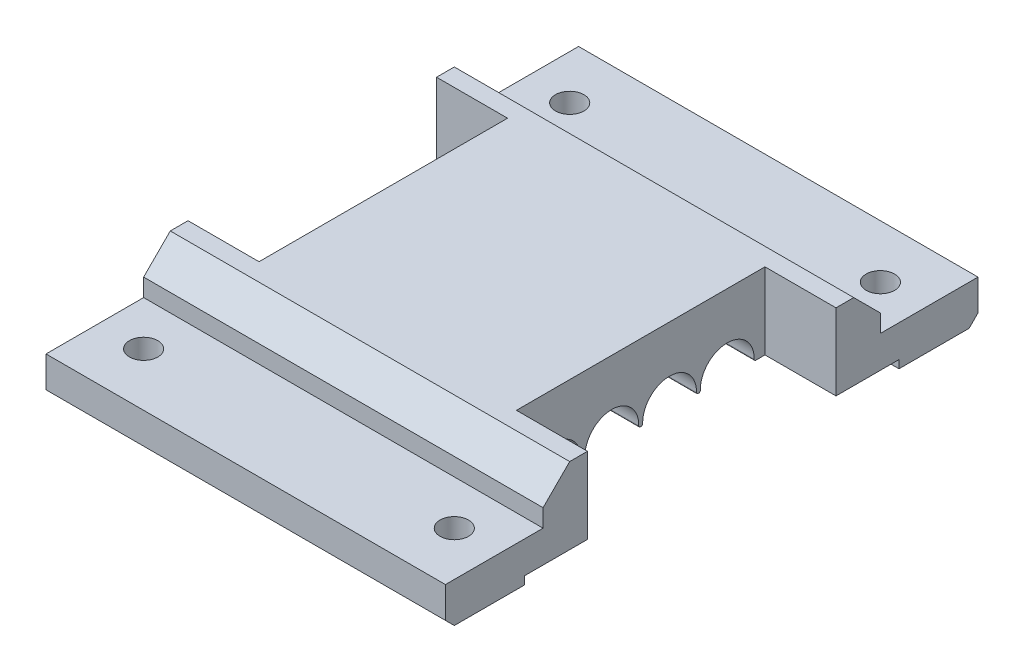
SolidWorks part; units mm, degrees
ref_plane "Front" through (0, 0, 0) normal (0, 0, 1) x (1, 0, 0)
ref_plane "Top" through (0, 0, 0) normal (0, 1, 0) x (1, 0, 0)
ref_plane "Right" through (0, 0, 0) normal (1, 0, 0) x (0, 0, -1)
sketch "Sketch1" plane through (0, 0, 0) normal (0, 1, 0) x (1, 0, 0)
  line L0 (0, -30) -> (0, 30) construction
  line L1 (-22.5, 30) -> (22.5, 30)
  line L2 (-22.5, 30) -> (-22.5, -30)
  line L3 (-22.5, -30) -> (22.5, -30)
  line L4 (22.5, 30) -> (22.5, -30)
  line L5 (-22.5, 30) -> (22.5, -30) construction
  line L6 (-22.5, -30) -> (22.5, 30) construction
  line L7 (-22.5, 24) -> (17.5, 24) construction
  line L8 (22.5, 0) -> (-22.5, 0) construction
  line L9 (17.5, 24) -> (17.5, -30) construction
  circle A0 centre (17.5, 24) radius 1.6
  circle A1 centre (-17.5, 24) radius 1.6
  circle A2 centre (-17.5, -24) radius 1.6
  circle A3 centre (17.5, -24) radius 1.6
  point P0 (0, 0)
  dimension "D1" = 60
extrude "Boss-Extrude1" add sketch "Sketch1" along normal blind 4.5
chamfer "Chamfer1" distance 1 angle 45 2 edges at (0, 0, -30) (0, 0, 30)
sketch "Sketch2" plane through (0, 0, 0) normal (1, 0, 0) x (0, 0, -1)
  line L1 (21.1, -0.9) -> (-21.1, -0.9)
  line L2 (21.1, -0.9) -> (21.1, 0.9)
  line L3 (21.1, 0.9) -> (-21.1, 0.9)
  line L4 (-21.1, -0.9) -> (-21.1, 0.9)
  line L5 (21.1, -0.9) -> (-21.1, 0.9) construction
  line L6 (21.1, 0.9) -> (-21.1, -0.9) construction
  point P0 (0, 0)
extrude "Cut-Extrude1" cut sketch "Sketch2" against normal through all both and the other way through all
sketch "Sketch3" plane through (0, 0, 0) normal (1, 0, 0) x (0, 0, -1)
  line L0 (18.8, -3.6) -> (-18.8, -3.6)
  line L1 (19, -3.4) -> (-19, -3.4)
  line L2 (-21.1, 0) -> (-21.1, 0.9)
  line L3 (-21, 0.9) -> (-21, -2.9)
  line L4 (20.8, -3.1) -> (-20.8, -3.1)
  line L5 (21, -2.9) -> (-21, -2.9)
  line L6 (-19.5, -3.1) -> (-19.5, 0.9)
  line L7 (-19, 6.5) -> (-19, 4.5)
  line L8 (-19, -3.1) -> (-19, -3.4)
  line L9 (21.1, 0.9) -> (12.979, 0.9)
  line L10 (19.5, 0.9) -> (12.762, 0.9)
  line L11 (6.521, 0.9) -> (6.479, 0.9)
  line L12 (6.738, 0.9) -> (6.2718, 0.9)
  line L13 (-0.0213, 0.9) -> (-0.238, 0.9)
  line L14 (-6.262, 0.9) -> (-6.7282, 0.9)
  line L15 (-6.479, 0.9) -> (-6.521, 0.9)
  line L16 (-13.0213, 0.9) -> (-19.5, 0.9)
  line L17 (-13.0213, 0.9) -> (-21.1, 0.9)
  line L18 (-16.5, -3.6) -> (-16.5, -3.1)
  line L19 (16, 9.5) -> (1.9528, 9.5)
  line L20 (-4.9695, 9.5) -> (-11.0472, 9.5)
  line L21 (-17.2502, 8.2498) -> (-19, 6.5)
  line L22 (19, 6.5) -> (16, 9.5)
  line L23 (16.5, -3.6) -> (16.5, -3.1)
  line L24 (19, -3.1) -> (19, -3.4)
  line L25 (19, 4.5) -> (19, 6.5)
  line L26 (19.5, -3.1) -> (19.5, 0.9)
  line L27 (21, 0.9) -> (21, -2.9)
  line L28 (21.1, 0) -> (21.1, 0.9)
  line L29 (12.314, -0.3291) -> (12.4926, -0.0188)
  line L30 (-13.1641, -3.6) -> (-13.1641, -3.1) construction
  arc A0 (-21, -2.9) -> (-20.8, -3.1) centre (-20.8, -2.9) ccw
  arc A1 (-19, -3.4) -> (-18.8, -3.6) centre (-18.8, -3.4) ccw
  arc A2 (-12.5076, -0.0255) -> (-11.4866, -1.2529) centre (-9.75, 1.23) ccw
  arc A3 (-1.5134, -1.2529) -> (-0.238, 0.9) centre (-3.25, 1.23) ccw
  arc A4 (-1.639, 3.7462) -> (-6.0484, 2.3419) centre (-3.25, 1.18) ccw
  arc A5 (-0.2209, 1.105) -> (-0.2215, 1.2756) centre (-3.25, 1.18) ccw
  arc A6 (-6.8667, 2.1113) -> (-7.2516, 2.8943) centre (-9.75, 1.18) ccw
  arc A7 (-1.5536, 3.6161) -> (-0.298, 1.4323) centre (-3.2862, 1.167) ccw
  arc A8 (-12.314, -0.3291) -> (-7.1135, 2.6631) centre (-9.7138, 1.167) ccw
  arc A9 (-6.7209, 1.105) -> (-6.521, 0.9) centre (-6.521, 1.1) ccw
  arc A10 (-6.479, 0.9) -> (-6.2791, 1.105) centre (-6.479, 1.1) ccw
  arc A11 (11.4866, -1.2529) -> (12.762, 0.9) centre (9.75, 1.23) ccw
  arc A12 (0.4924, -0.0255) -> (1.5134, -1.2529) centre (3.25, 1.23) ccw
  arc A13 (12.7791, 1.105) -> (6.9516, 2.3419) centre (9.75, 1.18) ccw
  arc A14 (6.1333, 2.1113) -> (5.7484, 2.8943) centre (3.25, 1.18) ccw
  circle A15 centre (9.7138, 1.167) radius 3
  arc A16 (0.686, -0.3291) -> (5.8865, 2.6631) centre (3.2862, 1.167) ccw
  arc A17 (-0.2209, 1.105) -> (-0.0213, 0.9) centre (-0.021, 1.1) ccw
  arc A18 (6.2791, 1.105) -> (6.479, 0.9) centre (6.479, 1.1) ccw
  arc A19 (6.521, 0.9) -> (6.7209, 1.105) centre (6.521, 1.1) ccw
  arc A20 (20.8, -3.1) -> (21, -2.9) centre (20.8, -2.9) ccw
  arc A21 (18.8, -3.6) -> (19, -3.4) centre (18.8, -3.4) ccw
  arc A22 (12.7791, 1.105) -> (12.979, 0.9) centre (12.979, 1.1) ccw
  dimension "D1" = 42.2
sketch "Sketch4" plane through (0, 0, 0) normal (1, 0, 0) x (0, 0, -1)
  line L17 (-19, 6.5) -> (-19, 4.5) construction
  line L18 (-17.2502, 8.2498) -> (-19, 6.5) construction
  line L24 (16, 9.5) -> (1.9528, 9.5) construction
  line L25 (19, 6.5) -> (16, 9.5) construction
  line L26 (19, 4.5) -> (19, 6.5) construction
  line L30 (19, 4.5) -> (-19, 4.5)
  line L47 (-19, 6.5) -> (-19, 4.5)
  line L48 (-16, 9.5) -> (-19, 6.5)
  line L54 (16, 9.5) -> (-16, 9.5)
  line L55 (19, 6.5) -> (16, 9.5)
  line L56 (19, 4.5) -> (19, 6.5)
extrude "Boss-Extrude2" add sketch "Sketch4" along normal through all and the other way through all
sketch "Sketch5" plane through (0, 0, 0) normal (1, 0, 0) x (0, 0, -1)
  line L7 (-6.479, 0.9) -> (-6.521, 0.9) construction
  line L12 (6.521, 0.9) -> (6.479, 0.9) construction
  line L30 (0, 0) -> (0, 1.4691) construction
  line L31 (-0.0213, 0.9) -> (0.0213, 0.9)
  line L32 (-12.979, 0.9) -> (-11.7206, -4.1299)
  line L33 (-11.7206, -4.1299) -> (11.7348, -2.9139)
  line L34 (11.7348, -2.9139) -> (12.979, 0.9)
  line L37 (-6.479, 0.9) -> (-6.521, 0.9)
  line L42 (6.521, 0.9) -> (6.479, 0.9)
  arc A0 (-1.639, 3.7462) -> (-6.0484, 2.3419) centre (-3.25, 1.18) ccw construction
  arc A1 (-12.7791, 1.105) -> (-12.979, 0.9) centre (-12.979, 1.1) cw
  arc A4 (-0.2209, 1.105) -> (-0.0213, 0.9) centre (-0.021, 1.1) ccw construction
  arc A11 (-6.7209, 1.105) -> (-6.521, 0.9) centre (-6.521, 1.1) ccw construction
  arc A12 (-6.479, 0.9) -> (-6.2791, 1.105) centre (-6.479, 1.1) ccw construction
  arc A15 (-6.8667, 2.1113) -> (-7.2516, 2.8943) centre (-9.75, 1.18) ccw construction
  arc A17 (6.1333, 2.1113) -> (5.7484, 2.8943) centre (3.25, 1.18) ccw construction
  arc A18 (12.7791, 1.105) -> (6.9516, 2.3419) centre (9.75, 1.18) ccw construction
  arc A19 (12.7791, 1.105) -> (12.979, 0.9) centre (12.979, 1.1) ccw construction
  arc A22 (6.2791, 1.105) -> (6.479, 0.9) centre (6.479, 1.1) ccw construction
  arc A23 (6.521, 0.9) -> (6.7209, 1.105) centre (6.521, 1.1) ccw construction
  arc A24 (-0.2209, 1.105) -> (-6.2791, 1.105) centre (-3.25, 1.18) ccw
  arc A25 (0.2209, 1.105) -> (0.0213, 0.9) centre (0.021, 1.1) cw
  arc A26 (-0.2209, 1.105) -> (-0.0213, 0.9) centre (-0.021, 1.1) ccw
  arc A33 (-6.7209, 1.105) -> (-6.521, 0.9) centre (-6.521, 1.1) ccw
  arc A34 (-6.479, 0.9) -> (-6.2791, 1.105) centre (-6.479, 1.1) ccw
  arc A37 (-6.7209, 1.105) -> (-12.7791, 1.105) centre (-9.75, 1.18) ccw
  arc A39 (6.2791, 1.105) -> (0.2209, 1.105) centre (3.25, 1.18) ccw
  arc A40 (12.7791, 1.105) -> (6.7209, 1.105) centre (9.75, 1.18) ccw
  arc A41 (12.7791, 1.105) -> (12.979, 0.9) centre (12.979, 1.1) ccw
  arc A44 (6.2791, 1.105) -> (6.479, 0.9) centre (6.479, 1.1) ccw
  arc A45 (6.521, 0.9) -> (6.7209, 1.105) centre (6.521, 1.1) ccw
extrude "Cut-Extrude2" cut sketch "Sketch5" against normal through all both and the other way through all
sketch "Sketch6" plane through (0, 9.5, 0) normal (0, 1, 0) x (1, 0, 0)
  line L0 (-31.1623, -14) -> (-14.5, -14)
  line L1 (27.1027, -14) -> (14.5, -14)
  line L2 (-31.1623, 14) -> (-31.1623, -14)
  line L3 (27.1027, -14) -> (27.1027, 14)
  line L11 (14.5, 14) -> (14.5, -14)
  line L44 (-31.1623, 14) -> (-14.5, 14)
  line L45 (27.1027, 14) -> (14.5, 14)
  line L47 (-14.5, 14) -> (-14.5, -14)
extrude "Cut-Extrude3" cut sketch "Sketch6" against normal blind 10
